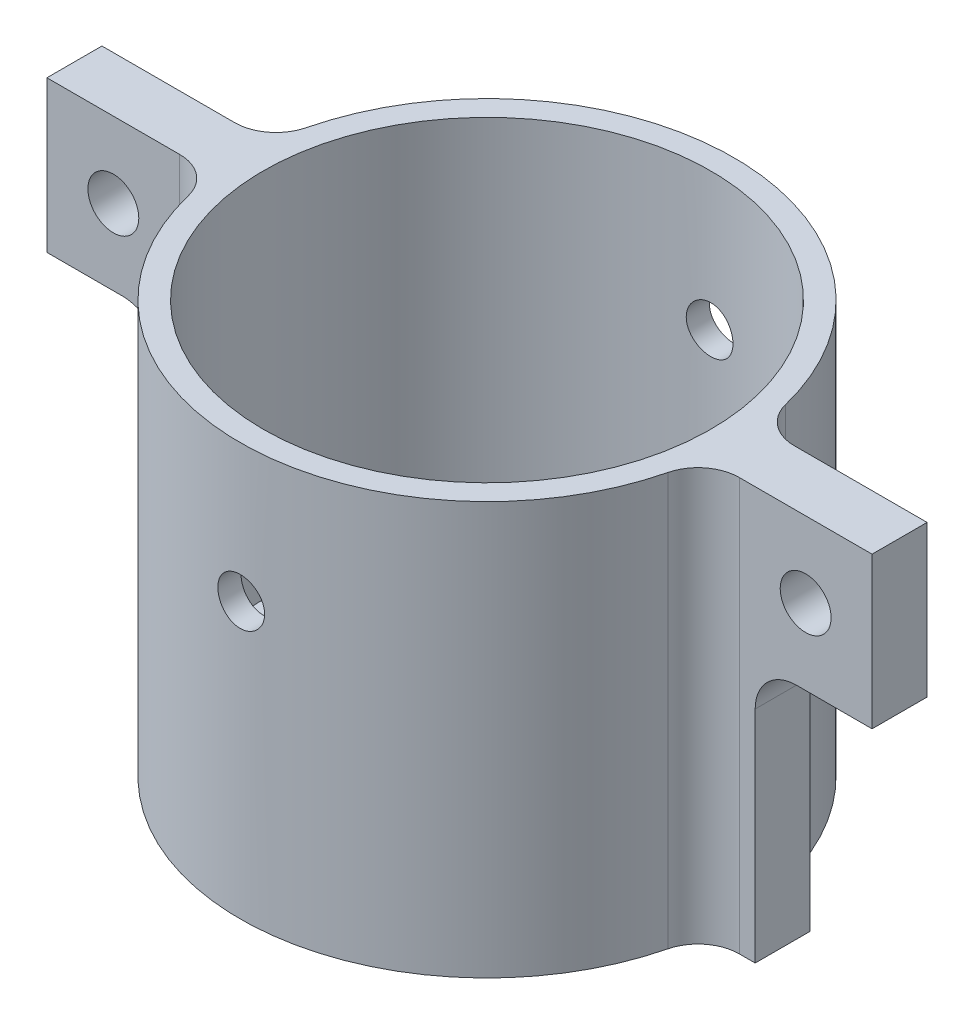
SolidWorks part; units mm, degrees
ref_plane "Front Plane" through (0, 0, 0) normal (0, 0, 1) x (1, 0, 0)
ref_plane "Top Plane" through (0, 0, 0) normal (0, 1, 0) x (1, 0, 0)
ref_plane "Right Plane" through (0, 0, 0) normal (1, 0, 0) x (0, 0, -1)
sketch "Sketch1" plane through (0, 0, 0) normal (0, 1, 0) x (1, 0, 0)
  line L5 (-31.3914, 0) -> (30.2135, 0) construction
  line L6 (-30, -2) -> (-30, 2)
  line L7 (-30, 2) -> (-17.8382, 2)
  line L8 (0, 28.1368) -> (0, -32.1926) construction
  line L9 (30, -2) -> (30, 2)
  line L10 (30, 2) -> (17.8382, 2)
  line L11 (-30, -2) -> (-17.8382, -2)
  line L12 (30, -2) -> (17.8382, -2)
  arc A4 (-17.8382, 2) -> (17.8382, 2) centre (0, 0) cw
  arc A5 (17.8382, -2) -> (-17.8382, -2) centre (0, 0) cw
  point P14 (-30, 0)
  point P16 (30, 0)
  dimension "D1" = 17.95
  dimension "D4" = 4
  dimension "D2" = 17.95
  dimension "D3" = 60
extrude "Boss-Extrude1" add sketch "Sketch1" along normal blind 30
sketch "Sketch4" plane through (-30, 0, 0) normal (-1, 0, 0) x (0, 0, 1)
  line L0 (2, 30) -> (2, 0) construction
  line L1 (-2, 0) -> (2, 0)
  line L2 (-2, 0) -> (-2, 19)
  line L3 (-2, 19) -> (2, 19)
  line L4 (2, 0) -> (2, 19)
  dimension "D1" = 19
extrude "Cut-Extrude3" cut sketch "Sketch4" against normal blind 8.5
ref_plane "Plane1" through (0, 0, 0) normal (1, 0, 0) x (0, 0, -1)
mirror "Mirror1" about plane through (0, 0, 0) normal (1, 0, 0) of "Cut-Extrude3"
sketch "Sketch6" plane through (0, 0, 0) normal (0, -1, 0) x (1, 0, 0)
  circle A0 centre (0, 0) radius 9
sketch "Sketch7" plane through (0, 30, 0) normal (0, 1, 0) x (1, 0, 0)
  circle A0 centre (0, 0) radius 16.275
  dimension "D1" = 32.55
extrude "Cut-Extrude4" cut sketch "Sketch7" against normal blind 27
extrude "Cut-Extrude5" cut sketch "Sketch6" against normal blind 4
fillet "Fillet3" radius 3 4 edges at (17.8382, 15, 2) (17.8382, 15, -2) (-17.8382, 15, 2) (-17.8382, 15, -2)
fillet "Fillet4" radius 3 2 edges at (-21.5, 19, 0) (21.5, 19, 0)
sketch "Sketch8" plane through (0, 0, -2) normal (0, 0, -1) x (-1, 0, 0)
  line L0 (-25.17, 25.48) -> (-25.17, 9.6984) construction
  line L1 (-30.8488, 24.5) -> (-19.4912, 24.5) construction
  line L2 (0, 40.2686) -> (0, -8.7145) construction
  line L3 (0, 2.2) -> (0, -2.2) construction
  line L4 (30.8488, 24.5) -> (19.4912, 24.5) construction
  line L5 (25.17, 25.48) -> (25.17, 9.6984) construction
  line L7 (-30, 30) -> (-20.3446, 30) construction
  line L10 (30, 30) -> (30, 19) construction
  circle A0 centre (-25.17, 24.5) radius 1.85
  circle A1 centre (25.17, 24.5) radius 1.85
  dimension "D1" = 5.5
  dimension "D4" = 3.7
  dimension "D2" = 4.83
  dimension "D3" = 0
extrude "Cut-Extrude6" cut sketch "Sketch8" against normal blind 4
ref_plane "Plane2" through (0, 0, -17.95) normal (0, 0, -1) x (-1, 0, 0)
sketch "Sketch9" plane through (0, 0, -17.95) normal (0, 0, -1) x (-1, 0, 0)
  line L0 (0, 30) -> (0, -9.7101) construction
  line L1 (17.4313, 30) -> (-17.4313, 30) construction
  line L2 (0, 2.2) -> (0, -2.2) construction
  line L3 (-32.3782, 20) -> (35.4769, 20) construction
  line L4 (-17.4313, 0) -> (17.4313, 0) construction
  circle A0 centre (0, 20) radius 1.7
  dimension "D1" = 20
  dimension "D2" = 3.4
extrude "Cut-Extrude7" cut sketch "Sketch9" against normal blind 37
equation "\"5.5.00mm\"=5"
